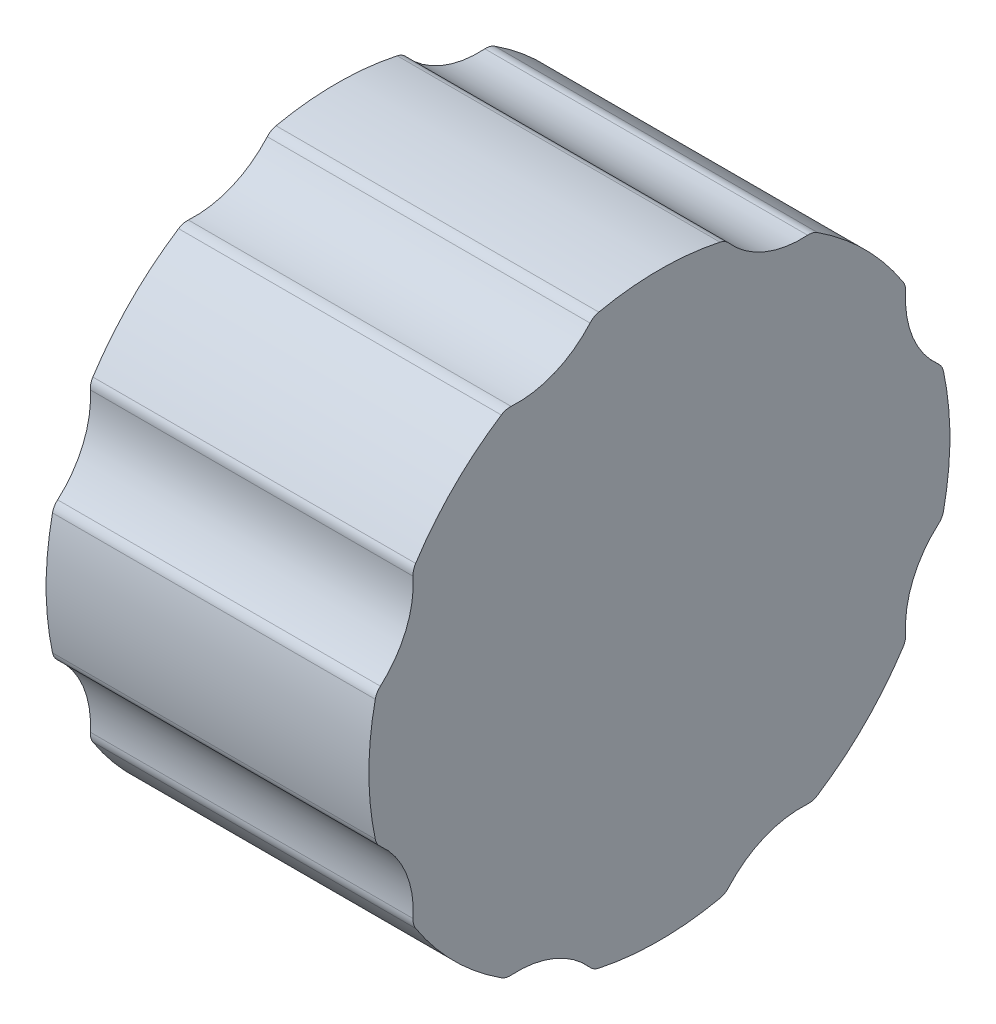
SolidWorks part; units mm, degrees
material "POM Acetal Copolymer"
ref_plane "Front Plane" through (0, 0, 0) normal (0, 0, 1) x (1, 0, 0)
ref_plane "Top Plane" through (0, 0, 0) normal (0, 1, 0) x (1, 0, 0)
ref_plane "Right Plane" through (0, 0, 0) normal (1, 0, 0) x (0, 0, -1)
sketch "Sketch1" plane through (0, 0, 0) normal (1, 0, 0) x (0, 0, -1)
  line L0 (1.25, 0) -> (0, 0) construction
  line L1 (0, 0) -> (-1.25, 0) construction
  line L2 (0, 0) -> (0, -5.1034) construction
  arc A0 (1.704, 1.6901) -> (-1.704, 1.6901) centre (0, 0) ccw
  circle A1 centre (0, 0) radius 9
  circle A2 centre (0, 0) radius 1.25 construction
  arc A3 (1.704, -1.6901) -> (1.704, 1.6901) centre (1.25, 0) ccw
  arc A6 (-1.704, 1.6901) -> (-1.704, -1.6901) centre (-1.25, 0) ccw
  arc A8 (-1.704, -1.6901) -> (1.704, -1.6901) centre (0, 0) ccw
  dimension "D1" = 4.8
  dimension "D2" = 18
  dimension "D3" = 3.5
  dimension "D4" = 2.5
  dimension "D5" = 180
extrude "Boss-Extrude1" add sketch "Sketch1" along normal blind 8
sketch "Sketch2" plane through (8, 0, 0) normal (1, 0, 0) x (0, 0, -1)
  circle A0 centre (0, 0) radius 9
  circle A1 centre (0, 0) radius 9 construction
extrude "Boss-Extrude2" add sketch "Sketch2" along normal blind 2
sketch "Sketch3" plane through (10, 0, 0) normal (1, 0, 0) x (0, 0, -1)
  line L3 (4.4009, 10.6246) -> (-4.4009, 10.6246) construction
  line L4 (-4.4009, 10.6246) -> (-10.6246, 4.4009) construction
  line L5 (-10.6246, 4.4009) -> (-10.6246, -4.4009) construction
  line L6 (-10.6246, -4.4009) -> (-4.4009, -10.6246) construction
  line L7 (-4.4009, -10.6246) -> (4.4009, -10.6246) construction
  line L8 (4.4009, -10.6246) -> (10.6246, -4.4009) construction
  line L9 (10.6246, -4.4009) -> (10.6246, 4.4009) construction
  line L10 (10.6246, 4.4009) -> (4.4009, 10.6246) construction
  circle A0 centre (-4.4009, 10.6246) radius 3
  circle A1 centre (4.4009, 10.6246) radius 3
  circle A2 centre (10.6246, 4.4009) radius 3
  circle A3 centre (4.4009, -10.6246) radius 3
  circle A4 centre (-10.6246, -4.4009) radius 3
  circle A5 centre (0, 0) radius 11.5 construction
  circle A6 centre (-10.6246, 4.4009) radius 3
  circle A7 centre (-4.4009, -10.6246) radius 3
  circle A8 centre (10.6246, -4.4009) radius 3
  dimension "D1" = 6
  dimension "D2" = 23
extrude "Cut-Extrude1" cut sketch "Sketch3" against normal through all
fillet "Fillet3" radius 0.5 16 edges at (5, -7.6449, -4.7492) (5, -8.764, -2.0475) (5, -4.7492, 7.6449) (5, -2.0475, 8.764) (5, 7.6449, 4.7492) (5, 8.764, 2.0475) (5, 4.7492, -7.6449) (5, 2.0475, -8.764) (5, 2.0475, 8.764) (5, 4.7492, 7.6449) (5, -8.764, 2.0475) (5, -7.6449, 4.7492) (5, -2.0475, -8.764) (5, -4.7492, -7.6449) (5, 8.764, -2.0475) (5, 7.6449, -4.7492)
sketch "Sketch4" plane through (0, 0, 0) normal (-1, 0, 0) x (0, 0, 1)
  circle A0 centre (0, 5.5) radius 1.75
  dimension "D1" = 3.5
  dimension "D2" = 5.5
extrude "Cut-Extrude2" cut sketch "Sketch4" against normal blind 8
sketch "Sketch5" plane through (0, 0, 0) normal (-1, 0, 0) x (0, 0, 1)
  circle A0 centre (0, 5.5) radius 2
  dimension "D1" = 4
extrude "Cut-Extrude3" cut sketch "Sketch5" against normal blind 2
